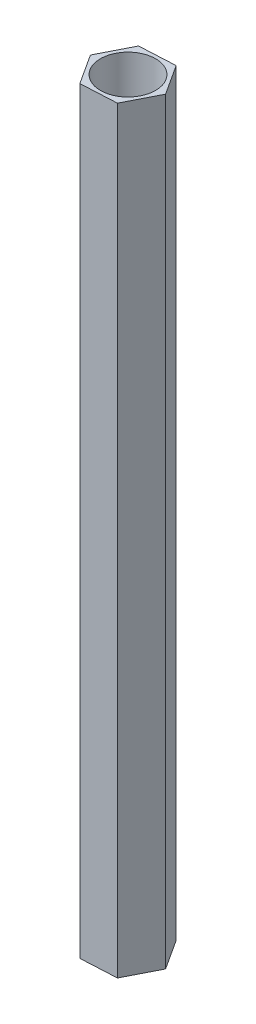
SolidWorks part; units mm, degrees
ref_plane "Front Plane" through (0, 0, 0) normal (0, 0, 1) x (1, 0, 0)
ref_plane "Top Plane" through (0, 0, 0) normal (0, 1, 0) x (1, 0, 0)
ref_plane "Right Plane" through (0, 0, 0) normal (1, 0, 0) x (0, 0, -1)
sketch "Sketch1" plane through (0, 0, 0) normal (0, 1, 0) x (1, 0, 0)
  line L1 (1.4133, -2.1801) -> (2.5946, 0.1339)
  line L2 (2.5946, 0.1339) -> (1.1813, 2.314)
  line L3 (1.1813, 2.314) -> (-1.4133, 2.1801)
  line L4 (-1.4133, 2.1801) -> (-2.5946, -0.1339)
  line L5 (-2.5946, -0.1339) -> (-1.1813, -2.314)
  line L6 (-1.1813, -2.314) -> (1.4133, -2.1801)
  circle A0 centre (0, 0) radius 2.25 construction
  circle A1 centre (0, 0) radius 2
  dimension "D1" = 4.5
  dimension "D2" = 4
extrude "Boss-Extrude1" add sketch "Sketch1" along normal blind 55
